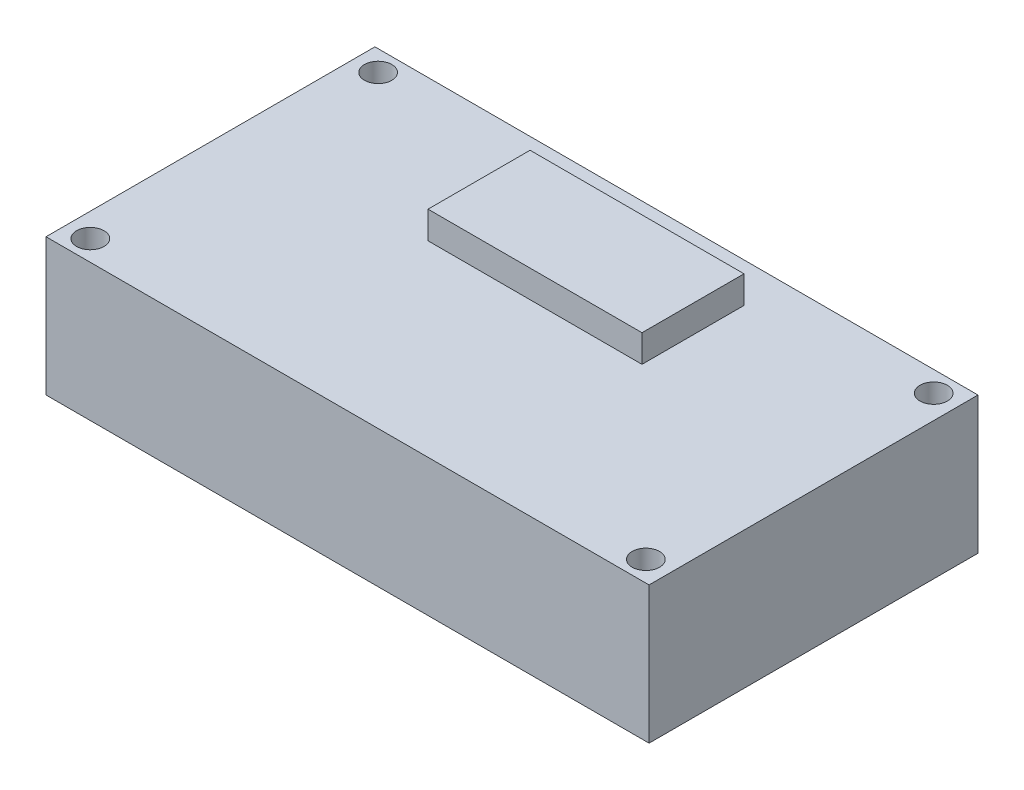
SolidWorks part; units mm, degrees
ref_plane "Front Plane" through (0, 0, 0) normal (0, 0, 1) x (1, 0, 0)
ref_plane "Top Plane" through (0, 0, 0) normal (0, 1, 0) x (1, 0, 0)
ref_plane "Right Plane" through (0, 0, 0) normal (1, 0, 0) x (0, 0, -1)
sketch "Sketch1" plane through (0, 0, 0) normal (0, 1, 0) x (1, 0, 0)
  line L1 (-33, -18) -> (33, -18)
  line L2 (-33, -18) -> (-33, 18)
  line L3 (-33, 18) -> (33, 18)
  line L4 (33, -18) -> (33, 18)
  line L5 (-33, -18) -> (33, 18) construction
  line L6 (-33, 18) -> (33, -18) construction
  point P0 (0, 0)
  dimension "D1" = 66
  dimension "D2" = 36
extrude "Boss-Extrude1" add sketch "Sketch1" along normal blind 15
sketch "Sketch2" plane through (0, 15, 0) normal (0, 1, 0) x (1, 0, 0)
  line L0 (33, -18) -> (33, 18) construction
  line L1 (-30.4, -15.75) -> (30.4, -15.75)
  line L2 (-30.4, -15.75) -> (-30.4, 15.75)
  line L3 (-30.4, 15.75) -> (30.4, 15.75)
  line L4 (30.4, -15.75) -> (30.4, 15.75)
  line L5 (-30.4, -15.75) -> (30.4, 15.75) construction
  line L6 (-30.4, 15.75) -> (30.4, -15.75) construction
  line L7 (33, 18) -> (-33, 18) construction
  line L8 (-33, -18) -> (33, -18) construction
  line L9 (-33, 18) -> (-33, -18) construction
  circle A0 centre (-30.4, 15.75) radius 1.5
  circle A1 centre (-30.4, -15.75) radius 1.5
  circle A2 centre (30.4, 15.75) radius 1.5
  circle A3 centre (30.4, -15.75) radius 1.5
  point P0 (0, 0)
  dimension "D5" = 3
  dimension "D6" = 3
  dimension "D7" = 3
  dimension "D8" = 3
  dimension "D1" = 2.6
  dimension "D2" = 2.25
  dimension "D3" = 2.25
  dimension "D4" = 2.6
extrude "Cut-Extrude1" cut sketch "Sketch2" against normal blind 15 contours A0 | A1 | A3 | A2
sketch "Sketch3" plane through (0, 15, 0) normal (0, 1, 0) x (1, 0, 0)
  line L1 (-11.7085, 2.5191) -> (11.7085, 2.5191)
  line L2 (-11.7085, 2.5191) -> (-11.7085, 13.6859)
  line L3 (-11.7085, 13.6859) -> (11.7085, 13.6859)
  line L4 (11.7085, 2.5191) -> (11.7085, 13.6859)
  line L5 (-11.7085, 2.5191) -> (11.7085, 13.6859) construction
  line L6 (-11.7085, 13.6859) -> (11.7085, 2.5191) construction
  point P0 (0, 8.1025)
extrude "Boss-Extrude2" add sketch "Sketch3" along normal blind 3
